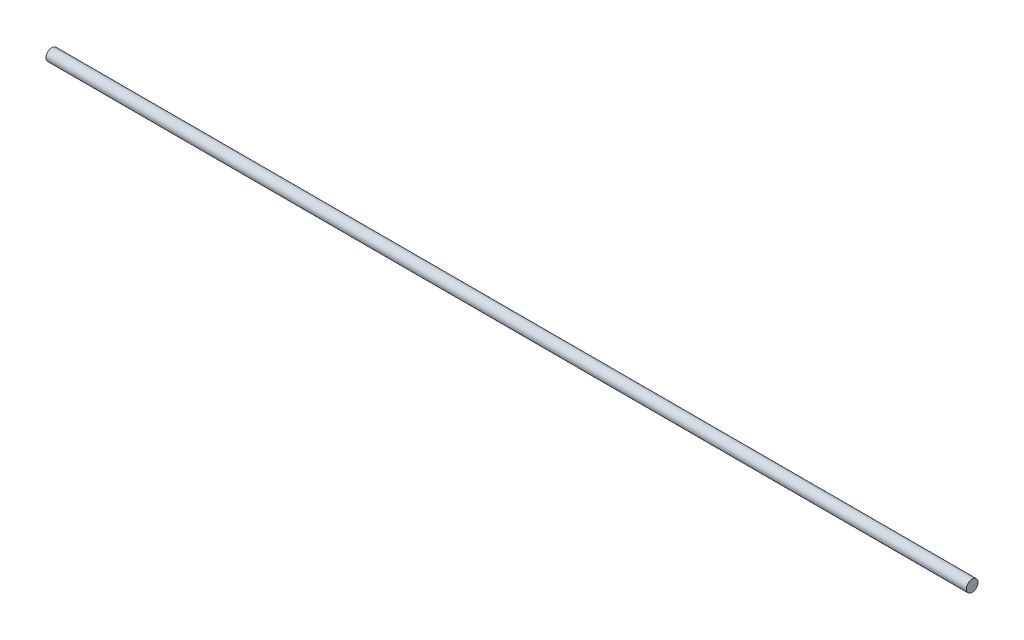
SolidWorks part; units mm, degrees
material "Hexcel AS4C (3000 Filaments)"
ref_plane "Front Plane" through (0, 0, 0) normal (0, 0, 1) x (1, 0, 0)
ref_plane "Top Plane" through (0, 0, 0) normal (0, 1, 0) x (1, 0, 0)
ref_plane "Right Plane" through (0, 0, 0) normal (1, 0, 0) x (0, 0, -1)
sketch "Sketch1" plane through (0, 0, 0) normal (1, 0, 0) x (0, 0, -1)
  circle A0 centre (0, 0) radius 5
  dimension "D1" = 10
extrude "Boss-Extrude1" add sketch "Sketch1" along normal mid plane 786
